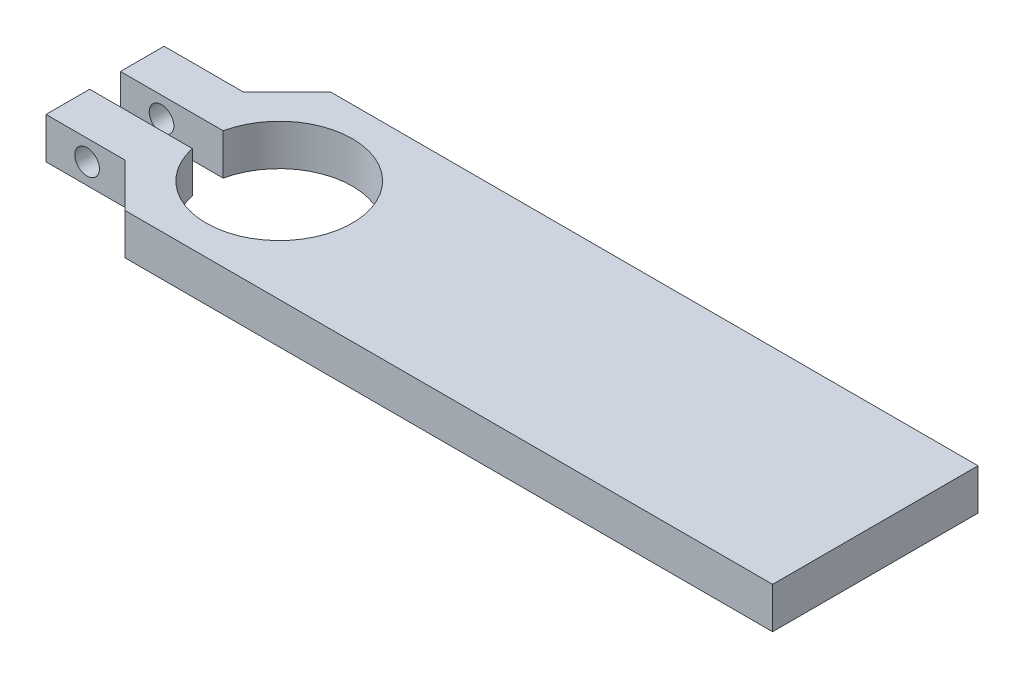
SolidWorks part; units mm, degrees
ref_plane "Front Plane" through (0, 0, 0) normal (0, 0, 1) x (1, 0, 0)
ref_plane "Top Plane" through (0, 0, 0) normal (0, 1, 0) x (1, 0, 0)
ref_plane "Right Plane" through (0, 0, 0) normal (1, 0, 0) x (0, 0, -1)
sketch "Sketch1" plane through (0, 0, 0) normal (0, 1, 0) x (1, 0, 0)
  line L1 (0, 0) -> (75, 0)
  line L2 (0, 0) -> (0, 20)
  line L3 (0, 20) -> (75, 20)
  line L4 (75, 0) -> (75, 20)
  dimension "D1" = 75
  dimension "D2" = 20
extrude "Boss-Extrude1" add sketch "Sketch1" along normal blind 4
sketch "Sketch2" plane through (0, 4, 0) normal (0, 1, 0) x (1, 0, 0)
  line L0 (0, 8.5) -> (10, 8.5)
  line L1 (0, 20) -> (0, 0) construction
  line L2 (0, 11.5) -> (10, 11.5)
  line L3 (0, 11.5) -> (0, 10)
  line L4 (0, 10) -> (0, 8.5)
  arc A0 (10, 11.5) -> (10, 8.5) centre (16.9602, 10) cw
  point P8 (22.0469, 14.5)
  point P9 (0, 0)
  point P10 (0, 0)
  point P11 (0, 0)
  dimension "D3" = 14.24
  dimension "D1" = 3
  dimension "D2" = 10
extrude "Cut-Extrude1" cut sketch "Sketch2" against normal blind 4 and the other way through all
hole_wizard "M2 Clearance Hole1" positions "Sketch3" profile "Sketch4" hole size "M2" standard "ISO" end condition through all
sketch "Sketch3" plane through (0, 0, -20) normal (0, 0, -1) x (-1, 0, 0)
  line L0 (-4, 4) -> (-4, 2) construction
  line L1 (-75, 4) -> (0, 4) construction
  line L2 (-4, 2) -> (-4, 0) construction
  line L3 (-75, 0) -> (0, 0) construction
  line L5 (0, 4) -> (0, 0) construction
  point P0 (-4, 2)
  dimension "D1" = 4
sketch "Sketch4" plane through (4, 2, -20) normal (1, 0, 0) x (0, 1, 0)
  line L0 (0, 0) -> (0, 20)
  line L1 (0, 20) -> (1.2, 20)
  line L2 (1.2, 20) -> (1.2, 0)
  line L5 (1.2, 0) -> (0, 0)
  line L11 (0, -6.35) -> (0, 107.95) construction
  dimension "Thru Hole Dia." = 2.4
  dimension "Thru Hole Depth" = 20
sketch "Sketch5" plane through (0, 4, 0) normal (0, 1, 0) x (1, 0, 0)
  line L0 (0, 20) -> (0, 11.5) construction
  line L1 (0, 15.75) -> (7.6913, 15.75)
  line L2 (7.6913, 15.75) -> (11.9413, 20)
  line L3 (75, 20) -> (0, 20) construction
  line L4 (11.9413, 20) -> (0, 20)
  line L5 (0, 20) -> (0, 15.75)
  line L6 (75, 10) -> (-7.0002, 10) construction
  line L8 (0, 0) -> (0, 4.25)
  line L9 (11.9413, 0) -> (0, 0)
  line L10 (7.6913, 4.25) -> (11.9413, 0)
  line L11 (0, 4.25) -> (7.6913, 4.25)
  arc A1 (10, 8.5) -> (10, 11.5) centre (16.9602, 10) ccw construction
  dimension "D1" = 135
  dimension "D2" = 3.5
extrude "Cut-Extrude2" cut sketch "Sketch5" against normal blind 4
